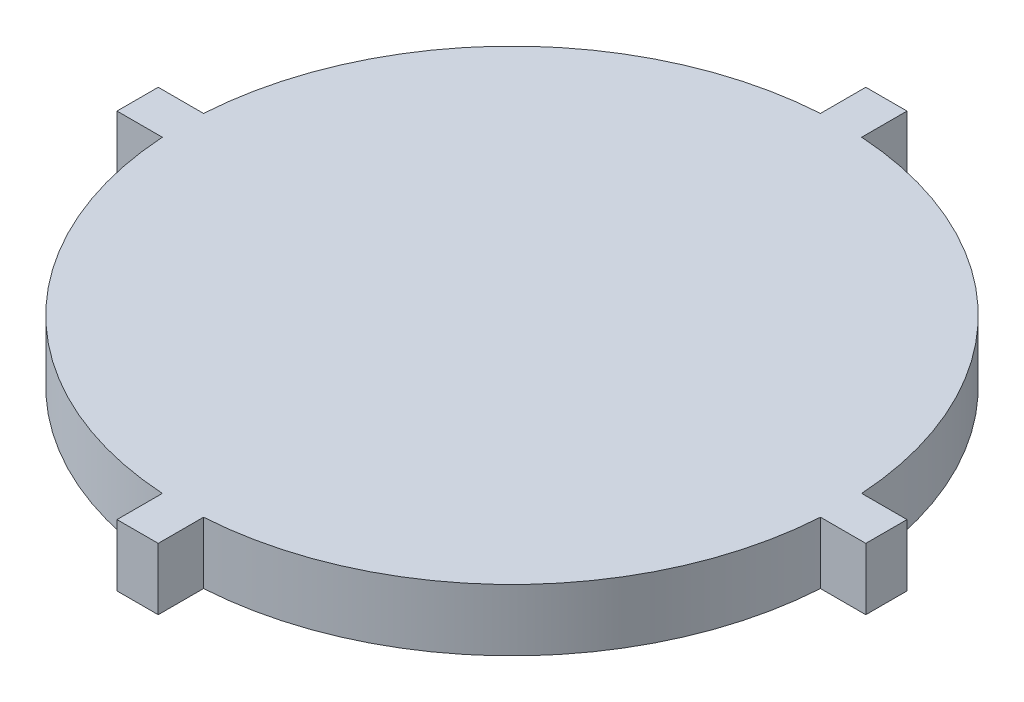
SolidWorks part; units mm, degrees
material "ABS"
ref_plane "Front Plane" through (0, 0, 0) normal (0, 0, 1) x (1, 0, 0)
ref_plane "Top Plane" through (0, 0, 0) normal (0, 1, 0) x (1, 0, 0)
ref_plane "Right Plane" through (0, 0, 0) normal (1, 0, 0) x (0, 0, -1)
other "Bounding Box"
ref_plane "Default Plane" through (-15.5039, 19.05, -142.8452) normal (-0.6267, 0, 0.7793) x (0.7793, 0, 0.6267)
sketch "Sketch1" plane through (0, 0, 0) normal (0, 1, 0) x (1, 0, 0)
  line L0 (-6.35, 115.3714) -> (6.35, 115.3714)
  line L1 (115.3714, -3.175) -> (115.3714, 6.35)
  line L2 (115.3714, -3.175) -> (115.3714, -6.35)
  line L3 (115.3714, 6.35) -> (101.4014, 6.35)
  line L4 (115.3714, -6.35) -> (101.4014, -6.35)
  line L6 (6.35, 101.4014) -> (6.35, 115.3714)
  line L7 (-6.35, -115.3714) -> (6.35, -115.3714)
  line L8 (-6.35, -101.4014) -> (-6.35, -115.3714)
  line L9 (6.35, -101.4014) -> (6.35, -115.3714)
  line L10 (-6.35, 101.4014) -> (-6.35, 115.3714)
  line L12 (-101.4014, 6.35) -> (-115.3714, 6.35)
  line L13 (-101.4014, -6.35) -> (-115.3714, -6.35)
  line L14 (-115.3714, 6.35) -> (-115.3714, -6.35)
  arc A1 (101.4014, 6.35) -> (6.35, 101.4014) centre (0, 0) ccw
  arc A2 (6.35, -101.4014) -> (101.4014, -6.35) centre (0, 0) ccw
  arc A3 (-101.4014, -6.35) -> (-6.35, -101.4014) centre (0, 0) ccw
  arc A4 (-6.35, 101.4014) -> (-101.4014, 6.35) centre (0, 0) ccw
  dimension "D1" = 12.7
  dimension "D2" = 203.2
  dimension "D3" = 12.7
  dimension "D4" = 13.97
  dimension "D5" = 13.97
  dimension "D6" = 12.7
  dimension "D7" = 13.97
  dimension "D8" = 13.97
  dimension "D9" = 13.97
  dimension "D10" = 13.97
  dimension "D11" = 13.97
  dimension "D12" = 13.97
  dimension "D13" = 12.7
extrude "Boss-Extrude1" add sketch "Sketch1" along normal blind 19.05
